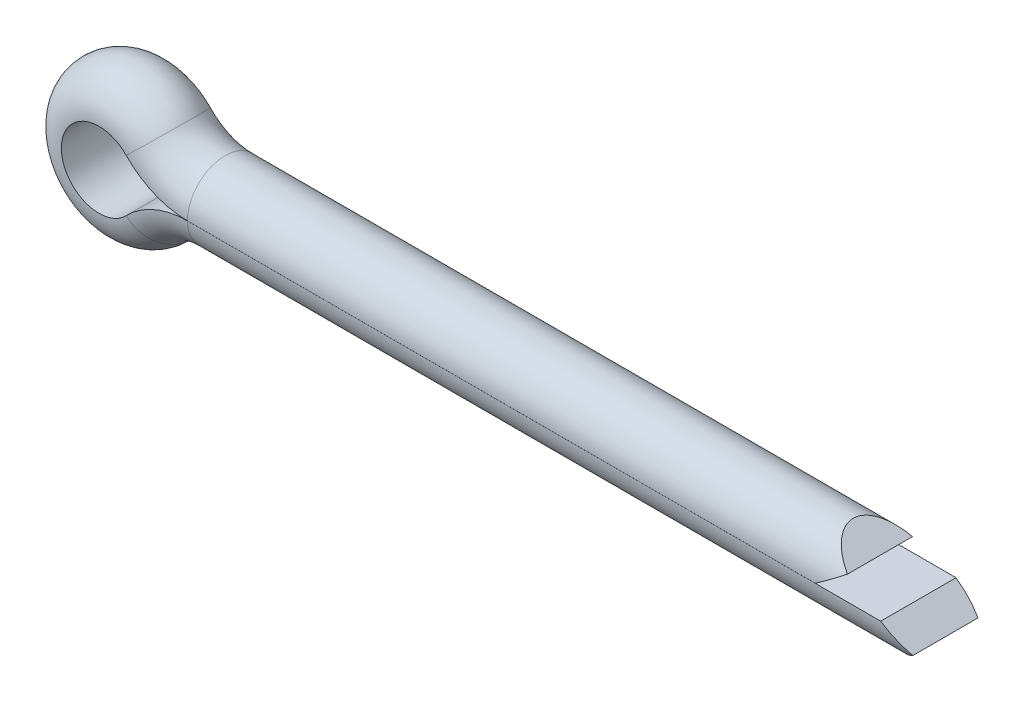
SolidWorks part; units mm, degrees
material "1.5714 (16NiCr4)"
ref_plane "Front" through (0, 0, 0) normal (0, 0, 1) x (1, 0, 0)
ref_plane "Top" through (0, 0, 0) normal (0, 1, 0) x (1, 0, 0)
ref_plane "Right" through (0, 0, 0) normal (1, 0, 0) x (0, 0, -1)
sketch "PathSke" plane through (0, 0, 0) normal (0, 0, 1) x (1, 0, 0)
  line L0 (40, 2.3) -> (0, 2.3)
  line L1 (0, -2.3) -> (44, -2.3)
  line L2 (0, 0) -> (49.7718, 0) construction
  line L3 (0, 0) -> (0, 16.5256) construction
  line L4 (-10, 0) -> (-10, 15.0279) construction
  arc A0 (0, 2.3) -> (-2.0832, 3.1873) centre (0, 5.1891) cw
  arc A1 (-2.0832, 3.1873) -> (-2.0832, -3.1873) centre (-5.4, 0) ccw
  arc A2 (-2.0832, -3.1873) -> (0, -2.3) centre (0, -5.1891) cw
  dimension "Diameter" = 4.6
  dimension "Head_dia" = 9.2
  dimension "Head_ht" = 10
  dimension "Length" = 40
  dimension "Tip_offset" = 4
ref_plane "SectionPlane" through (40, 0, 0) normal (1, 0, 0) x (0, 0, -1)
sketch "SectionSke" plane through (40, 0, 0) normal (1, 0, 0) x (0, 0, -1)
  line L1 (-2.3, 0.002) -> (2.3, 0.002)
  arc A0 (2.3, 0.002) -> (-2.3, 0.002) centre (0, 0) ccw
  dimension "Diameter" = 4.6
  dimension "D1" = 0.002
sweep "Body" add profiles "SectionSke" path "PathSke"
sketch "ConeCutSke" plane through (0, 0, 0) normal (0, 0, 1) x (1, 0, 0)
  line L0 (0, 0) -> (0, 16.2682) construction
  line L1 (0, 0) -> (75.9079, 0) construction
  line L2 (0, 0) -> (44, 0) construction
  line L3 (40, 1.151) -> (38.3533, 2.31)
  line L4 (40, 0.002) -> (40, 2.3) construction
  line L6 (40, 1.151) -> (38.3477, 0)
  line L7 (44, -1.151) -> (42.3477, 0)
  line L8 (44, -2.3) -> (44, -0.002) construction
  line L9 (44, -1.151) -> (42.3533, -2.31)
  line L10 (42.3477, 0) -> (38.3477, 0)
  line L11 (38.3533, 2.31) -> (44.01, 2.31)
  line L12 (44.01, 2.31) -> (44.01, -2.31)
  line L13 (44.01, -2.31) -> (42.3533, -2.31)
  line L14 (40, 2.3) -> (0, 2.3) construction
  dimension "D1" = 0.01
  dimension "D2" = 0.01
  dimension "D3" = 70
  dimension "D4" = 70
extrude "ConeCut" cut sketch "ConeCutSke" against normal through all and the other way through all
equation "' \"Diameter@PathSke\" = 9.5"
equation "' \"Head_dia@PathSke\" = 19"
equation "' \"Head_ht@PathSke\" = 20"
equation "' \"Tip_offset@PathSke\" = 6.3"
equation "' \"Length@PathSke\" = 45"
equation "' \"Diameter@PathSke\" = 1"
equation "' \"Head_dia@PathSke\" = 2"
equation "' \"Head_ht@PathSke\" = 3"
equation "' \"Tip_offset@PathSke\" = 2.5"
equation "' \"Length@PathSke\" = 8"
equation "' \"Diameter@PathSke\" = 0.5"
equation "' \"Head_dia@PathSke\" = 1"
equation "' \"Head_ht@PathSke\" = 2"
equation "' \"Tip_offset@PathSke\" = 1.6"
equation "' \"Length@PathSke\" = 4"
equation "\"Diameter@SectionSke\" = \"Diameter@PathSke\""
equation "\"Length@SectionPlane\" = \"Length@PathSke\""
